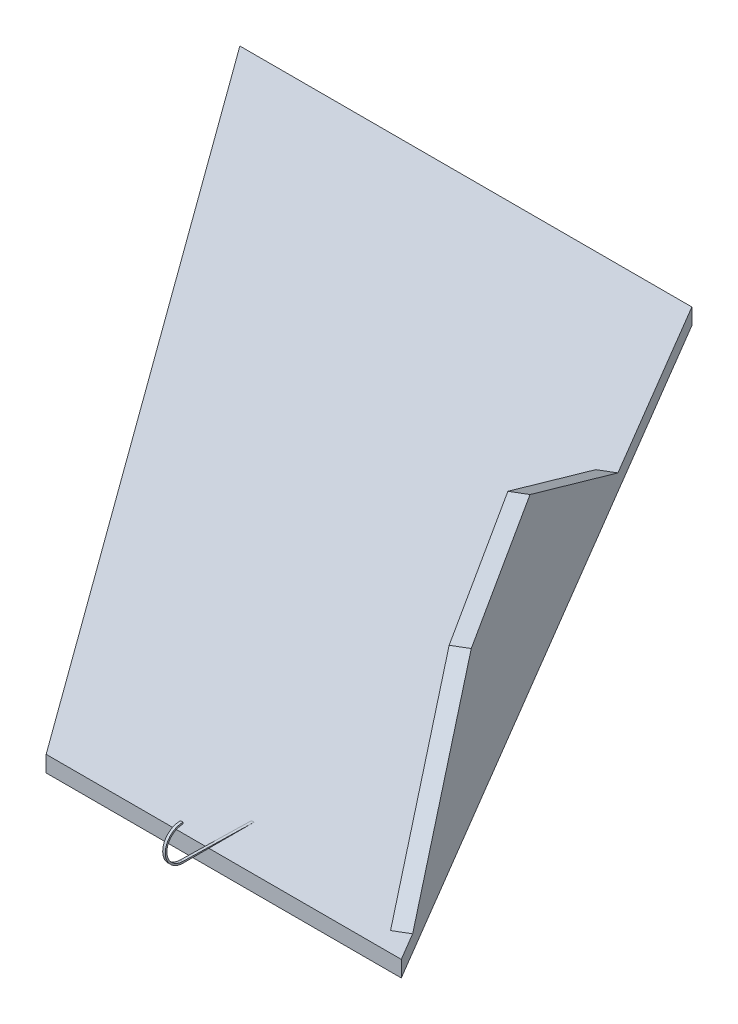
SolidWorks part; units mm, degrees
ref_plane "前视基准面" through (0, 0, 0) normal (0, 0, 1) x (1, 0, 0)
ref_plane "上视基准面" through (0, 0, 0) normal (0, 1, 0) x (1, 0, 0)
ref_plane "右视基准面" through (0, 0, 0) normal (1, 0, 0) x (0, 0, -1)
sketch "Sketch" plane through (0, 0, 0) normal (0, 1, 0) x (1, 0, 0)
  line L0 (0, 0) -> (0, 279.4)
  line L1 (0, 279.4) -> (533.4, 279.4)
  line L3 (0, 0) -> (533.4, 0)
  line L4 (533.4, 279.4) -> (533.4, 0)
  point P0 (0, 0)
  dimension "D1" = 533.4
  dimension "D2" = 279.4
extrude "Extrude" add sketch "Sketch" along normal blind 6.35 contours L3 L4 L1 L0
sketch "草图2" plane through (0, 0, 0) normal (0, 0, 1) x (1, 0, 0)
  line L1 (0, 0) -> (533.4, 0)
  line L2 (0, 0) -> (0, 55.88)
  line L3 (0, 55.88) -> (533.4, 55.88)
  line L4 (533.4, 0) -> (533.4, 55.88)
  line L5 (0, 6.35) -> (0, 0) construction
  dimension "D1" = 55.88
extrude "凸台-拉伸2" [suppressed] add sketch "草图2" along normal blind 12.7
chamfer "Chamfer1" [suppressed] distance 7.62 angle 45
sketch "Sketch1" [suppressed] plane through (533.4, 0, 0) normal (1, 0, 0) x (0, 0, -1)
  line L0 (0, 55.88) -> (0, 12.7)
  line L1 (0, 12.7) -> (43.18, 12.7)
  line L2 (360.68, 12.7) -> (0, 12.7) construction
  line L3 (43.18, 12.7) -> (0, 55.88)
extrude "Extrude1" [suppressed] add sketch "Sketch1" against normal blind 12.7
sketch "Sketch4" [suppressed] plane through (0, 0, 0) normal (-1, 0, 0) x (0, 0, 1)
  line L0 (0, 55.88) -> (0, 12.7)
  line L1 (0, 55.88) -> (0, 12.7) construction
  line L2 (0, 12.7) -> (-43.18, 12.7)
  line L3 (0, 12.7) -> (-360.68, 12.7) construction
  line L4 (-43.18, 12.7) -> (0, 55.88)
extrude "Extrude3" [suppressed] add sketch "Sketch4" against normal blind 12.7 contours L4 L0 L2
ref_plane "Plane1" through (266.7, 0, 0) normal (-1, 0, 0) x (0, 0, 1)
sketch "Sketch5" plane through (266.7, 0, 0) normal (-1, 0, 0) x (0, 0, 1)
  line L0 (0, 6.35) -> (10.16, 6.35)
  line L1 (10.16, 13.335) -> (10.16, 19.685) construction
  line L2 (10.16, 19.685) -> (10.16, 20.32)
  line L3 (10.3039, 6.9866) -> (-17.78, 6.35)
  line L4 (-17.78, 6.35) -> (0, 6.35)
  arc A0 (10.16, 6.35) -> (10.16, 20.32) centre (10.16, 13.335) ccw
  arc A1 (10.3039, 6.9866) -> (10.16, 19.685) centre (10.16, 13.335) ccw
  dimension "D1" = 6.35
  dimension "D2" = 6.985
  dimension "D3" = 17.78
  dimension "D4" = 10.16
extrude "Extrude4" add sketch "Sketch5" along normal blind 0.508 and the other way blind 0.508 contours A1 L2 A0 L0 L4 L3
sketch "Sketch6" plane through (0, 0, 0) normal (0, -1, 0) x (1, 0, 0)
  line L0 (185.553, -266.2795) -> (177.8, -279.4)
  line L1 (0, 0) -> (533.4, 0) construction
  line L2 (0, -279.4) -> (533.4, -279.4) construction
  line L3 (185.42, -279.4) -> (533.4, -279.4)
  line L4 (533.4, -279.4) -> (533.4, 0)
  line L5 (533.4, 0) -> (342.9, 0)
  line L6 (177.8, -279.4) -> (185.42, -279.4)
  line L7 (342.9, 0) -> (185.553, -266.2795)
  line L8 (0, 0) -> (203.2, 0)
  line L9 (203.2, 0) -> (0, -279.4)
  line L10 (0, -279.4) -> (0, 0)
  point P15 (0, 0)
  dimension "D1" = 190.5
  dimension "D2" = 355.6
  dimension "D3" = 7.62
  dimension "D4" = 15.24
  dimension "D5" = 203.2
extrude "Extrude5" cut sketch "Sketch6" against normal blind 76.2
sketch "Sketch7" plane through (254.1556, 0, -150.1828) normal (0.8609, 0, -0.5087) x (-0.5087, 0, -0.8609)
  line L0 (-161.7433, 6.35) -> (-62.5772, 85.6915)
  line L1 (-62.5772, 85.6915) -> (67.5408, 6.35)
  line L2 (-174.4433, 6.35) -> (150.0908, 6.35) construction
  line L3 (-161.7433, 6.35) -> (67.5408, 6.35)
  dimension "D1" = 152.4
  dimension "D2" = 127
  dimension "D3" = 12.7
  dimension "D4" = 82.55
extrude "Extrude6" add sketch "Sketch7" against normal blind 6.35
sketch "Sketch8" plane through (254.1556, 0, -150.1828) normal (0.8609, 0, -0.5087) x (-0.5087, 0, -0.8609)
  line L0 (-96.2936, 58.7154) -> (-30.6842, 66.2443)
  line L1 (-62.5772, 85.6915) -> (-161.7433, 6.35) construction
  line L2 (67.5408, 6.35) -> (-62.5772, 85.6915) construction
  line L3 (-30.6842, 66.2443) -> (-62.5772, 85.6915)
  line L4 (-62.5772, 85.6915) -> (-96.2936, 58.7154)
  dimension "D1" = 43.18
  dimension "D2" = 66.04
extrude "Cut-Extrude1" cut sketch "Sketch8" against normal blind 23.368
